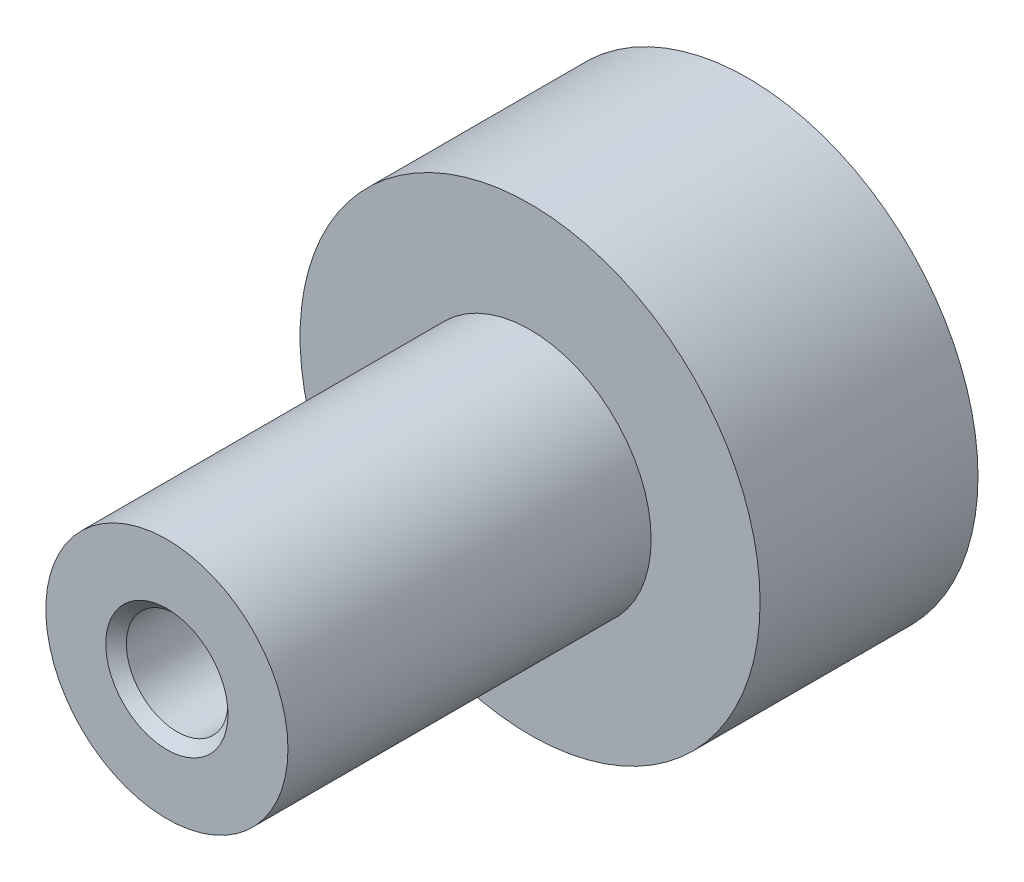
SolidWorks part; units mm, degrees
ref_plane "Front Plane" through (0, 0, 0) normal (0, 0, 1) x (1, 0, 0)
ref_plane "Top Plane" through (0, 0, 0) normal (0, 1, 0) x (1, 0, 0)
ref_plane "Right Plane" through (0, 0, 0) normal (1, 0, 0) x (0, 0, -1)
sketch "Sketch1" plane through (0, 0, 0) normal (0, 0, 1) x (1, 0, 0)
  circle A0 centre (0, 0) radius 8
  circle A1 centre (0, 0) radius 9.5
  dimension "D1" = 16
  dimension "D2" = 19
extrude "Boss-Extrude1" add sketch "Sketch1" along normal blind 6
sketch "Sketch2" plane through (0, 0, 6) normal (0, 0, 1) x (1, 0, 0)
  circle A0 centre (0, 0) radius 9.5
  dimension "D1" = 19
extrude "Boss-Extrude2" add sketch "Sketch2" along normal blind 3
sketch "Sketch3" plane through (0, 0, 9) normal (0, 0, 1) x (1, 0, 0)
  circle A1 centre (0, 0) radius 5
  dimension "D2" = 10
extrude "Boss-Extrude3" add sketch "Sketch3" along normal blind 15
sketch "Sketch4" plane through (0, 0, 0) normal (0, 0, -1) x (-1, 0, 0)
  line L0 (0, 0) -> (-8.4519, 2.2647) construction
  line L1 (0, 0) -> (-2.2647, 8.4519) construction
  line L2 (0, 0) -> (0, 9.5) construction
  line L3 (-7.7274, 2.0706) -> (-8.4519, 2.2647)
  line L4 (-2.0706, 7.7274) -> (-2.2647, 8.4519)
  circle A0 centre (0, 0) radius 8.75 construction
  circle A1 centre (0, 0) radius 9.5 construction
  arc A2 (-8.4519, 2.2647) -> (-2.2647, 8.4519) centre (0, 0) cw
  arc A3 (-7.7274, 2.0706) -> (-2.0706, 7.7274) centre (0, 0) cw
  circle A4 centre (0, 0) radius 8 construction
  dimension "D1" = 17.5
  dimension "D2" = 60
  dimension "D3" = 15
extrude "Cut-Extrude1" cut sketch "Sketch4" against normal up to surface (6 mm away) up to face at (8, 0, 6)
pattern_circular "CirPattern1" count 5 over 360 about axis through (0, 0, 0) along (0, 0, 1) of "Cut-Extrude1"
hole_wizard "M5 Tapped Hole1" positions "Sketch5" profile "Sketch7" tap size "M5" standard "ISO"
sketch "Sketch5" plane through (0, 0, 24) normal (0, 0, 1) x (1, 0, 0)
  point P0 (0, 0)
cosmetic thread "Hole Thread1"
sketch "Sketch7" plane through (0, 0, 24) normal (1, 0, 0) x (0, -1, 0)
  line L0 (0, 0) -> (0, 16.2618)
  line L1 (0, 16.2618) -> (2.1, 15)
  line L2 (2.1, 15) -> (2.1, 0.425)
  line L3 (2.1, 0.425) -> (2.525, 0)
  line L5 (2.525, 0) -> (0, 0)
  line L6 (-2.1, 0.425) -> (-2.525, 0) construction
  line L10 (0, 16.2618) -> (-2.1, 15) construction
  line L11 (0, -6.35) -> (0, 107.95) construction
  dimension "Tap Drill Dia." = 4.2
  dimension "Tap Drill Depth" = 15
  dimension "Near C'Sink Dia." = 5.05
  dimension "Near C'Sink Angle" = 90
  dimension "Drill Angle" = 118
